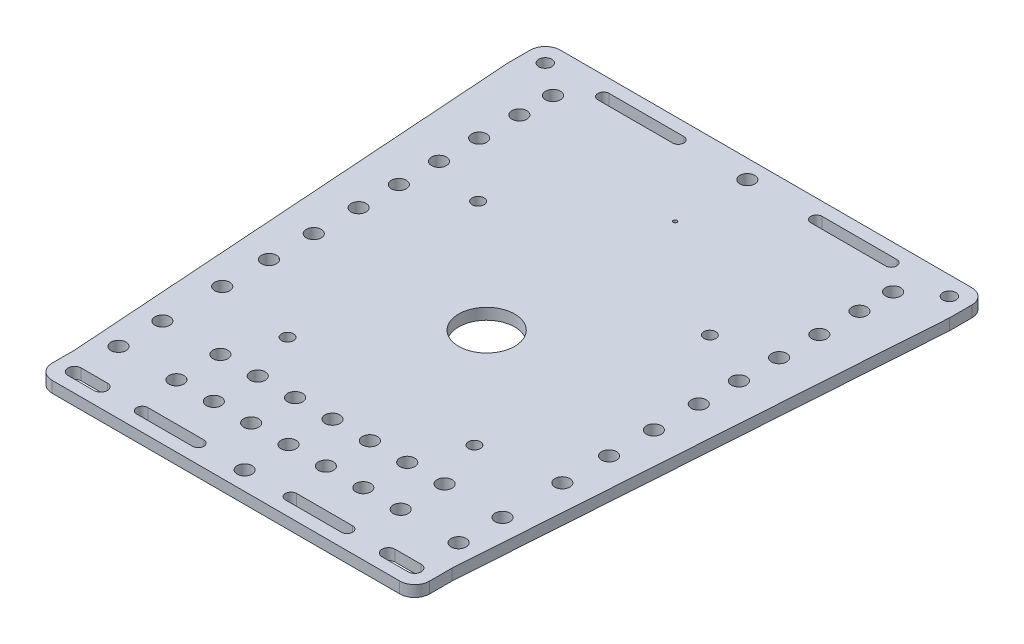
SolidWorks part; units mm, degrees
ref_plane "Front Plane" through (0, 0, 0) normal (0, 0, 1) x (1, 0, 0)
ref_plane "Top Plane" through (0, 0, 0) normal (0, 1, 0) x (1, 0, 0)
ref_plane "Right Plane" through (0, 0, 0) normal (1, 0, 0) x (0, 0, -1)
sketch "Sketch1" plane through (0, 0, 0) normal (0, 1, 0) x (1, 0, 0)
  line L0 (-12.0664, 0) -> (96.0664, 0)
  line L1 (42, 0) -> (42, -134.5)
  line L2 (-3.5, -134.5) -> (87.5, -134.5)
  line L3 (-17.0664, -5) -> (-8.5, -129.5)
  line L8 (-17.0664, 0) -> (-17.0664, 5)
  line L9 (-17.0664, 5) -> (96.0664, 5)
  line L10 (96.0664, 5) -> (101.0664, 5)
  line L11 (101.0664, 5) -> (101.0664, -5)
  line L13 (-17.0664, -5) -> (-17.0664, 0)
  line L14 (101.0664, -5) -> (92.5, -129.5)
  line L15 (-8.5, -134.5) -> (-8.5, -129.5)
  line L18 (92.5, -129.5) -> (92.5, -139.5)
  line L19 (92.5, -139.5) -> (-8.5, -139.5)
  line L20 (-8.5, -139.5) -> (-8.5, -134.5)
  line L21 (-3.5, -132.75) -> (3.5, -132.75)
  line L22 (-3.5, -136.25) -> (3.5, -136.25)
  line L23 (87.5, -132.75) -> (80.5, -132.75)
  line L24 (80.5, -136.25) -> (87.5, -136.25)
  circle A0 centre (-12.0664, 0) radius 1.75
  circle A1 centre (96.0664, 0) radius 1.75
  arc A2 (-3.5, -132.75) -> (-3.5, -136.25) centre (-3.5, -134.5) ccw
  arc A3 (87.5, -136.25) -> (87.5, -132.75) centre (87.5, -134.5) ccw
  arc A4 (3.5, -136.25) -> (3.5, -132.75) centre (3.5, -134.5) ccw
  arc A5 (80.5, -132.75) -> (80.5, -136.25) centre (80.5, -134.5) ccw
extrude "Boss-Extrude2" add sketch "Sketch1" along normal blind 3
sketch "Sketch2" plane through (0, 3, 0) normal (0, 1, 0) x (1, 0, 0)
  line L4 (11, -41.0284) -> (73, -41.0284)
  line L5 (73, -41.0284) -> (67, -98.0284)
  line L6 (67, -98.0284) -> (17, -98.0284)
  line L7 (17, -98.0284) -> (11, -41.0284)
  circle A0 centre (11, -41.0284) radius 1.6
  circle A1 centre (73, -41.0284) radius 1.6
  circle A2 centre (17, -98.0284) radius 1.6
  circle A3 centre (67, -98.0284) radius 1.6
extrude "Cut-Extrude1" cut sketch "Sketch2" against normal blind 3 contours A0 | A3 | A1 | A2
fillet "Fillet1" radius 4 4 edges at (-8.5, 1.5, 139.5) (92.5, 1.5, 139.5) (101.0664, 1.5, -5) (-17.0664, 1.5, -5)
sketch "Sketch3" plane through (0, 3, 0) normal (0, 1, 0) x (1, 0, 0)
  line L3 (54.3976, -134.5) -> (69.3976, -134.5) construction
  line L4 (29.6024, -134.5) -> (14.6024, -134.5) construction
  line L5 (23.5197, 0) -> (3.5197, 0) construction
  line L6 (23.5197, -1.5) -> (3.5197, -1.5)
  line L7 (23.5197, 1.5) -> (3.5197, 1.5)
  line L8 (29.6024, -136) -> (14.6024, -136)
  line L9 (29.6024, -133) -> (14.6024, -133)
  line L10 (54.3976, -136) -> (69.3976, -136)
  line L11 (54.3976, -133) -> (69.3976, -133)
  line L12 (60.4803, 0) -> (80.4803, 0) construction
  line L13 (60.4803, -1.5) -> (80.4803, -1.5)
  line L14 (60.4803, 1.5) -> (80.4803, 1.5)
  circle A0 centre (42, 0) radius 2
  circle A1 centre (-3.5, -95) radius 2
  circle A2 centre (-3.5, -111) radius 2
  circle A3 centre (42, -134.5) radius 2
  arc A4 (23.5197, -1.5) -> (23.5197, 1.5) centre (23.5197, 0) ccw
  arc A5 (3.5197, 1.5) -> (3.5197, -1.5) centre (3.5197, 0) ccw
  arc A6 (29.6024, -136) -> (29.6024, -133) centre (29.6024, -134.5) ccw
  arc A7 (14.6024, -133) -> (14.6024, -136) centre (14.6024, -134.5) ccw
  circle A8 centre (-3.5, -122.75) radius 2
  circle A10 centre (12, -111) radius 2
  circle A11 centre (22, -111) radius 2
  circle A12 centre (32, -111) radius 2
  circle A13 centre (42, -111) radius 2
  arc A14 (54.3976, -136) -> (54.3976, -133) centre (54.3976, -134.5) cw
  arc A15 (69.3976, -133) -> (69.3976, -136) centre (69.3976, -134.5) cw
  arc A16 (60.4803, -1.5) -> (60.4803, 1.5) centre (60.4803, 0) cw
  arc A17 (80.4803, 1.5) -> (80.4803, -1.5) centre (80.4803, 0) cw
  circle A18 centre (52, -111) radius 2
  circle A19 centre (62, -111) radius 2
  circle A20 centre (72, -111) radius 2
  circle A21 centre (87.5, -122.75) radius 2
  circle A22 centre (87.5, -111) radius 2
  circle A23 centre (87.5, -95) radius 2
  point P9 (13.5197, 0)
  point P14 (22.1024, -134.5)
  point P27 (61.8976, -134.5)
  point P48 (70.4803, 0)
extrude "Cut-Extrude2" cut sketch "Sketch3" against normal blind 3
sketch "Sketch4" plane through (0, 3, 0) normal (0, 1, 0) x (1, 0, 0)
  circle A0 centre (12, -122.75) radius 2
  circle A1 centre (22, -122.75) radius 2
  circle A2 centre (32, -122.75) radius 2
  circle A3 centre (42, -122.75) radius 2
  circle A4 centre (52, -122.75) radius 2
  circle A5 centre (62, -122.75) radius 2
  circle A6 centre (72, -122.75) radius 2
extrude "Cut-Extrude3" cut sketch "Sketch4" against normal blind 3
sketch "Sketch7" plane through (0, 3, 0) normal (0, 1, 0) x (1, 0, 0)
  circle A0 centre (42, -69.75) radius 7.5
extrude "Cut-Extrude5" cut sketch "Sketch7" against normal blind 3 contours A0
sketch "Sketch8" plane through (0, 3, 0) normal (0, 1, 0) x (1, 0, 0)
  line L6 (91.3284, -138.3284) -> (-7.3284, -138.3284)
  circle A1 centre (-3.5, -82.5) radius 2
  circle A2 centre (-3.5, -70.5) radius 2
  circle A3 centre (-3.5, -58.5) radius 2
  circle A4 centre (-3.5, -47.75) radius 2
  circle A5 centre (-3.5, -37) radius 2
  circle A6 centre (-3.5, -26.25) radius 2
  circle A7 centre (-3.5, -15.5) radius 2
  circle A8 centre (-3.5, -6.5) radius 2
  circle A13 centre (87.5, -6.5) radius 2
  arc A14 (88.5, -139.5) -> (92.5, -135.5) centre (88.5, -135.5) ccw construction
  arc A15 (-8.5, -135.5) -> (-4.5, -139.5) centre (-4.5, -135.5) ccw construction
  circle A16 centre (87.5, -15.5) radius 2
  circle A17 centre (87.5, -26.25) radius 2
  circle A18 centre (87.5, -37) radius 2
  circle A19 centre (87.5, -47.75) radius 2
  circle A20 centre (87.5, -58.5) radius 2
  circle A21 centre (87.5, -70.5) radius 2
  circle A22 centre (87.5, -82.5) radius 2
  point P0 (0, 0)
extrude "Cut-Extrude7" cut sketch "Sketch8" against normal blind 3 contours A6 | A5 | A2 | A1 | A8 | A7 | A4 | A3 | A13 | A16 | A17 | A18 | A19 | A20 | A21 | A22
sketch "Sketch9" plane through (0, 3, 0) normal (0, 1, 0) x (1, 0, 0)
  circle A1 centre (42, -19.3106) radius 0.5
extrude "Cut-Extrude8" cut sketch "Sketch9" against normal blind 3 contours A1
